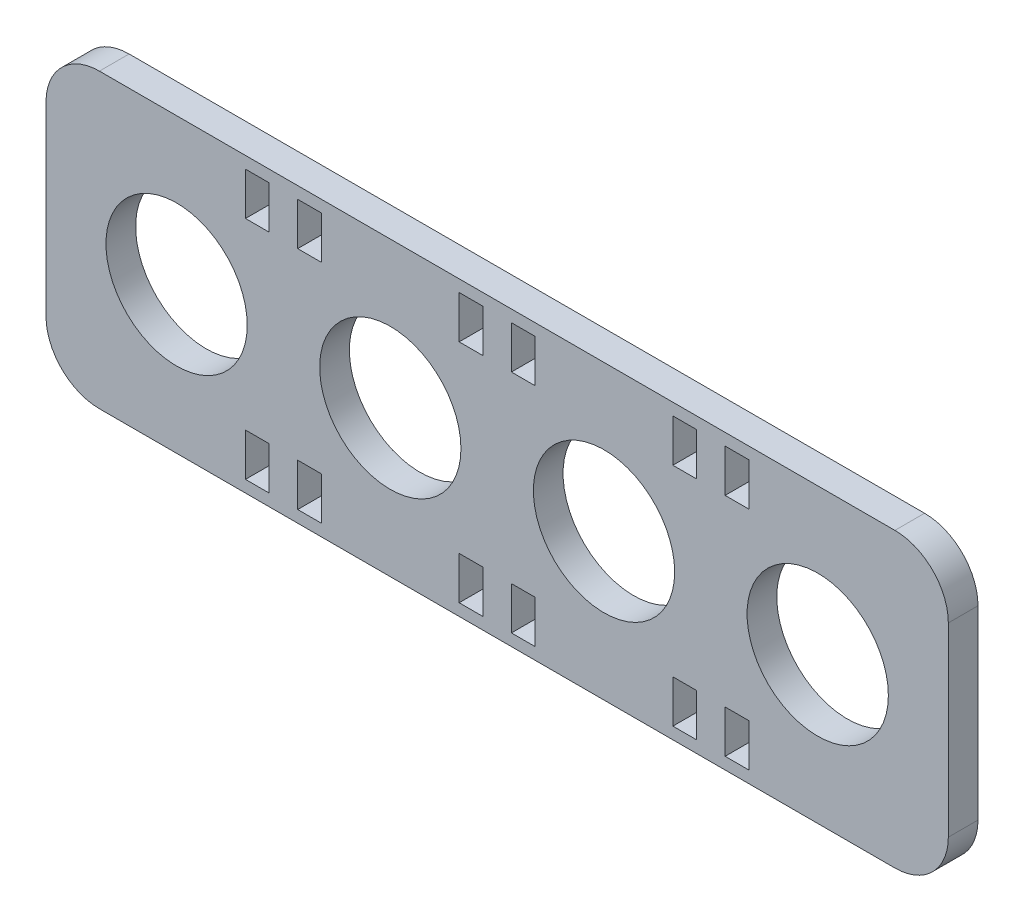
SolidWorks part; units mm, degrees
ref_plane "Front Plane" through (0, 0, 0) normal (0, 0, 1) x (1, 0, 0)
ref_plane "Top Plane" through (0, 0, 0) normal (0, 1, 0) x (1, 0, 0)
ref_plane "Right Plane" through (0, 0, 0) normal (1, 0, 0) x (0, 0, -1)
sketch "Sketch1" plane through (0, 0, 0) normal (0, 0, 1) x (1, 0, 0)
  line L0 (12.065, -6.2325) -> (22.86, -12.465)
  line L5 (34.925, -6.2325) -> (45.72, -12.465)
  line L7 (-10.795, -6.2325) -> (0, -12.465)
  line L8 (0, -12.465) -> (10.795, -6.2325)
  line L9 (10.795, -6.2325) -> (10.795, 6.2325)
  line L10 (10.795, 6.2325) -> (0, 12.465)
  line L11 (0, 12.465) -> (-10.795, 6.2325)
  line L12 (-10.795, 6.2325) -> (-10.795, -6.2325)
  line L13 (22.86, -12.465) -> (33.655, -6.2325)
  line L14 (33.655, -6.2325) -> (33.655, 6.2325)
  line L15 (33.655, 6.2325) -> (22.86, 12.465)
  line L16 (22.86, 12.465) -> (12.065, 6.2325)
  line L17 (12.065, 6.2325) -> (12.065, -6.2325)
  line L24 (0, 0) -> (0, 12.465) construction
  line L37 (45.72, -12.465) -> (56.515, -6.2325)
  line L38 (56.515, -6.2325) -> (56.515, 6.2325)
  line L39 (56.515, 6.2325) -> (45.72, 12.465)
  line L40 (45.72, 12.465) -> (34.925, 6.2325)
  line L41 (34.925, 6.2325) -> (34.925, -6.2325)
  line L42 (57.785, -6.2325) -> (68.58, -12.465)
  line L43 (68.58, -12.465) -> (79.375, -6.2325)
  line L44 (79.375, -6.2325) -> (79.375, 6.2325)
  line L45 (79.375, 6.2325) -> (68.58, 12.465)
  line L46 (68.58, 12.465) -> (57.785, 6.2325)
  line L47 (57.785, 6.2325) -> (57.785, -6.2325)
  line L49 (-8.255, 12.465) -> (76.835, 12.465)
  line L50 (-10.795, 9.925) -> (-10.795, -9.925)
  line L51 (-8.255, -12.465) -> (76.835, -12.465)
  line L52 (79.375, 9.925) -> (79.375, -9.925)
  line L53 (-8.255, 15.64) -> (76.835, 15.64)
  line L54 (82.55, 9.925) -> (82.55, -9.925)
  line L55 (-8.255, -15.64) -> (76.835, -15.64)
  line L56 (-13.97, 9.925) -> (-13.97, -9.925)
  line L57 (10.795, 6.2325) -> (12.065, 6.2325) construction
  line L59 (11.43, 6.2325) -> (11.43, 15.64) construction
  line L60 (11.43, 14.37) -> (12.954, 14.37) construction
  line L61 (7.366, 14.37) -> (7.366, 9.798)
  line L62 (12.954, 14.37) -> (15.494, 14.37)
  line L63 (12.954, 14.37) -> (12.954, 9.798)
  line L64 (12.954, 9.798) -> (15.494, 9.798)
  line L65 (15.494, 14.37) -> (15.494, 9.798)
  line L66 (9.906, 9.798) -> (7.366, 9.798)
  line L67 (9.906, 14.37) -> (9.906, 9.798)
  line L68 (9.906, 14.37) -> (7.366, 14.37)
  line L69 (0, 0) -> (-13.97, 0) construction
  line L70 (30.226, 14.37) -> (30.226, 9.798)
  line L71 (32.766, 9.798) -> (30.226, 9.798)
  line L72 (32.766, 14.37) -> (32.766, 9.798)
  line L73 (32.766, 14.37) -> (30.226, 14.37)
  line L74 (35.814, 14.37) -> (38.354, 14.37)
  line L75 (35.814, 14.37) -> (35.814, 9.798)
  line L76 (35.814, 9.798) -> (38.354, 9.798)
  line L77 (38.354, 14.37) -> (38.354, 9.798)
  line L78 (53.086, 14.37) -> (53.086, 9.798)
  line L79 (55.626, 9.798) -> (53.086, 9.798)
  line L80 (55.626, 14.37) -> (55.626, 9.798)
  line L81 (55.626, 14.37) -> (53.086, 14.37)
  line L82 (58.674, 14.37) -> (61.214, 14.37)
  line L83 (58.674, 14.37) -> (58.674, 9.798)
  line L84 (58.674, 9.798) -> (61.214, 9.798)
  line L85 (61.214, 14.37) -> (61.214, 9.798)
  line L86 (61.214, -14.37) -> (61.214, -9.798)
  line L87 (58.674, -9.798) -> (61.214, -9.798)
  line L88 (58.674, -14.37) -> (58.674, -9.798)
  line L89 (58.674, -14.37) -> (61.214, -14.37)
  line L90 (55.626, -14.37) -> (53.086, -14.37)
  line L91 (55.626, -14.37) -> (55.626, -9.798)
  line L92 (55.626, -9.798) -> (53.086, -9.798)
  line L93 (53.086, -14.37) -> (53.086, -9.798)
  line L94 (38.354, -14.37) -> (38.354, -9.798)
  line L95 (35.814, -9.798) -> (38.354, -9.798)
  line L96 (35.814, -14.37) -> (35.814, -9.798)
  line L97 (35.814, -14.37) -> (38.354, -14.37)
  line L98 (32.766, -14.37) -> (30.226, -14.37)
  line L99 (32.766, -14.37) -> (32.766, -9.798)
  line L100 (32.766, -9.798) -> (30.226, -9.798)
  line L101 (30.226, -14.37) -> (30.226, -9.798)
  line L102 (15.494, -14.37) -> (15.494, -9.798)
  line L103 (12.954, -9.798) -> (15.494, -9.798)
  line L104 (12.954, -14.37) -> (12.954, -9.798)
  line L105 (12.954, -14.37) -> (15.494, -14.37)
  line L106 (9.906, -14.37) -> (7.366, -14.37)
  line L107 (9.906, -14.37) -> (9.906, -9.798)
  line L108 (9.906, -9.798) -> (7.366, -9.798)
  line L109 (7.366, -14.37) -> (7.366, -9.798)
  line L111 (9.906, 14.37) -> (12.954, 14.37)
  line L112 (9.906, 14.37) -> (9.906, 9.798)
  line L113 (9.906, 9.798) -> (12.954, 9.798)
  line L114 (12.954, 14.37) -> (12.954, 9.798)
  line L115 (32.766, 14.37) -> (35.814, 14.37)
  line L116 (32.766, 14.37) -> (32.766, 9.798)
  line L117 (32.766, 9.798) -> (35.814, 9.798)
  line L118 (35.814, 14.37) -> (35.814, 9.798)
  line L119 (55.626, 14.37) -> (58.674, 14.37)
  line L120 (55.626, 14.37) -> (55.626, 9.798)
  line L121 (55.626, 9.798) -> (58.674, 9.798)
  line L122 (58.674, 14.37) -> (58.674, 9.798)
  line L123 (55.626, -9.798) -> (58.674, -9.798)
  line L124 (55.626, -9.798) -> (55.626, -14.37)
  line L125 (55.626, -14.37) -> (58.674, -14.37)
  line L126 (58.674, -9.798) -> (58.674, -14.37)
  line L127 (32.766, -9.798) -> (35.814, -9.798)
  line L128 (32.766, -9.798) -> (32.766, -14.37)
  line L129 (32.766, -14.37) -> (35.814, -14.37)
  line L130 (35.814, -9.798) -> (35.814, -14.37)
  line L131 (9.906, -9.798) -> (12.954, -9.798)
  line L132 (9.906, -9.798) -> (9.906, -14.37)
  line L133 (9.906, -14.37) -> (12.954, -14.37)
  line L134 (12.954, -9.798) -> (12.954, -14.37)
  circle A0 centre (0, 0) radius 7.5565
  circle A1 centre (0, 0) radius 10.795 construction
  circle A2 centre (22.86, 0) radius 7.5565
  circle A3 centre (22.86, 0) radius 10.795 construction
  circle A5 centre (45.72, 0) radius 7.5565
  arc A7 (-8.255, 12.465) -> (-10.795, 9.925) centre (-8.255, 9.925) ccw
  circle A10 centre (45.72, 0) radius 10.795 construction
  circle A11 centre (68.58, 0) radius 7.5565
  circle A12 centre (68.58, 0) radius 10.795 construction
  arc A13 (79.375, 9.925) -> (76.835, 12.465) centre (76.835, 9.925) ccw
  arc A14 (-10.795, -9.925) -> (-8.255, -12.465) centre (-8.255, -9.925) ccw
  arc A15 (79.375, -9.925) -> (76.835, -12.465) centre (76.835, -9.925) cw
  arc A16 (82.55, 9.925) -> (76.835, 15.64) centre (76.835, 9.925) ccw
  arc A17 (82.55, -9.925) -> (76.835, -15.64) centre (76.835, -9.925) cw
  arc A18 (-13.97, -9.925) -> (-8.255, -15.64) centre (-8.255, -9.925) ccw
  arc A19 (-8.255, 15.64) -> (-13.97, 9.925) centre (-8.255, 9.925) ccw
  point P0 (0, 0)
  point P3 (45.72, 0)
  point P8 (22.86, 0)
  point P36 (68.58, 0)
  point P57 (-45.72, 0)
  dimension "D1" = 15.113
  dimension "D8" = 3.175
  dimension "D5" = 2.54
  dimension "D6" = 2.54
  dimension "D7" = 2.54
  dimension "D2" = 21.59
  dimension "D4" = 22.86
  dimension "D9" = 24.93
  dimension "D10" = 1.524
  dimension "D11" = 2.54
  dimension "D12" = 1.27
  dimension "D13" = 4.572
  dimension "D15" = 22.86
  dimension "D3" = 4
  dimension "D14" = 3
extrude "Boss-Extrude1" add sketch "Sketch1" along normal blind 3.175
